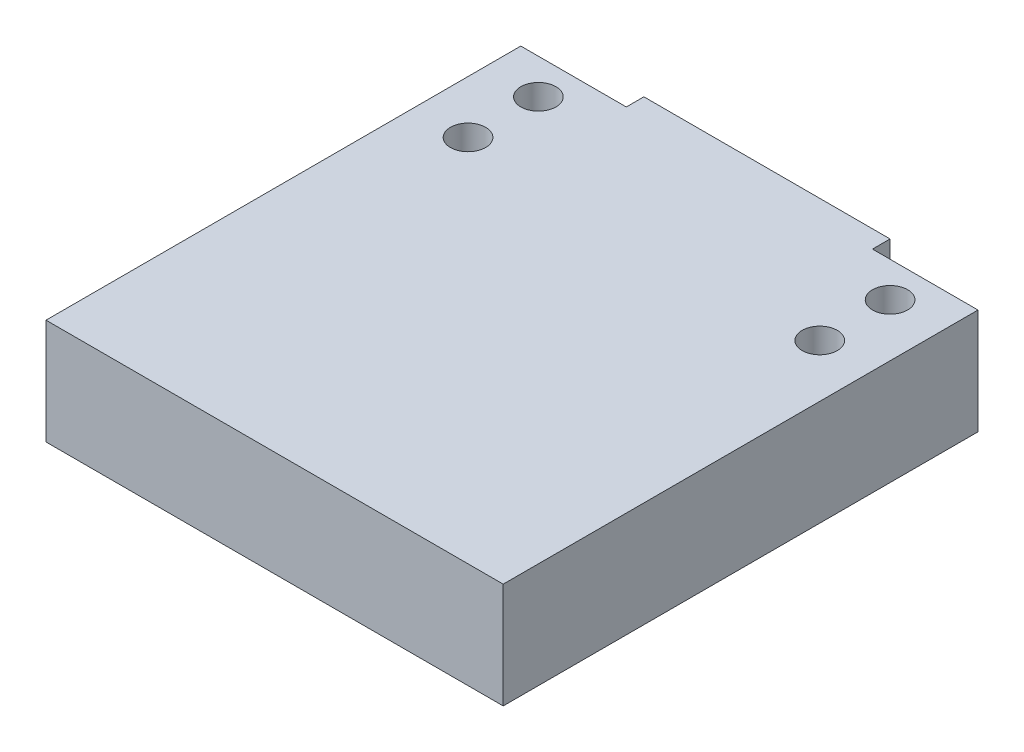
SolidWorks part; units mm, degrees
ref_plane "Front Plane" through (0, 0, 0) normal (0, 0, 1) x (1, 0, 0)
ref_plane "Top Plane" through (0, 0, 0) normal (0, 1, 0) x (1, 0, 0)
ref_plane "Right Plane" through (0, 0, 0) normal (1, 0, 0) x (0, 0, -1)
sketch "Sketch1" plane through (0, 0, 0) normal (0, 1, 0) x (1, 0, 0)
  line L0 (0, 27) -> (6, 27)
  line L1 (0, 0) -> (26, 0)
  line L2 (0, 0) -> (0, 27)
  line L3 (6, 28) -> (20, 28)
  line L4 (26, 0) -> (26, 27)
  line L5 (6, 27) -> (6, 28)
  line L6 (20, 28) -> (20, 27)
  line L7 (20, 27) -> (26, 27)
  dimension "D1" = 6
  dimension "D2" = 6
  dimension "D3" = 26
  dimension "D4" = 28
  dimension "D5" = 1
extrude "Boss-Extrude1" add sketch "Sketch1" along normal blind 6
sketch "Sketch2" plane through (0, 6, 0) normal (0, 1, 0) x (1, 0, 0)
  line L0 (6, 27) -> (0, 27) construction
  line L1 (0, 27) -> (0, 0) construction
  line L2 (26, 0) -> (26, 27) construction
  circle A0 centre (3, 25) radius 1
  circle A1 centre (23, 25) radius 1
  circle A2 centre (3, 21) radius 1
  circle A3 centre (23, 21) radius 1
  dimension "D1" = 2
  dimension "D2" = 2
  dimension "D3" = 3
  dimension "D4" = 3
  dimension "D5" = 4
extrude "Cut-Extrude1" cut sketch "Sketch2" against normal through all
